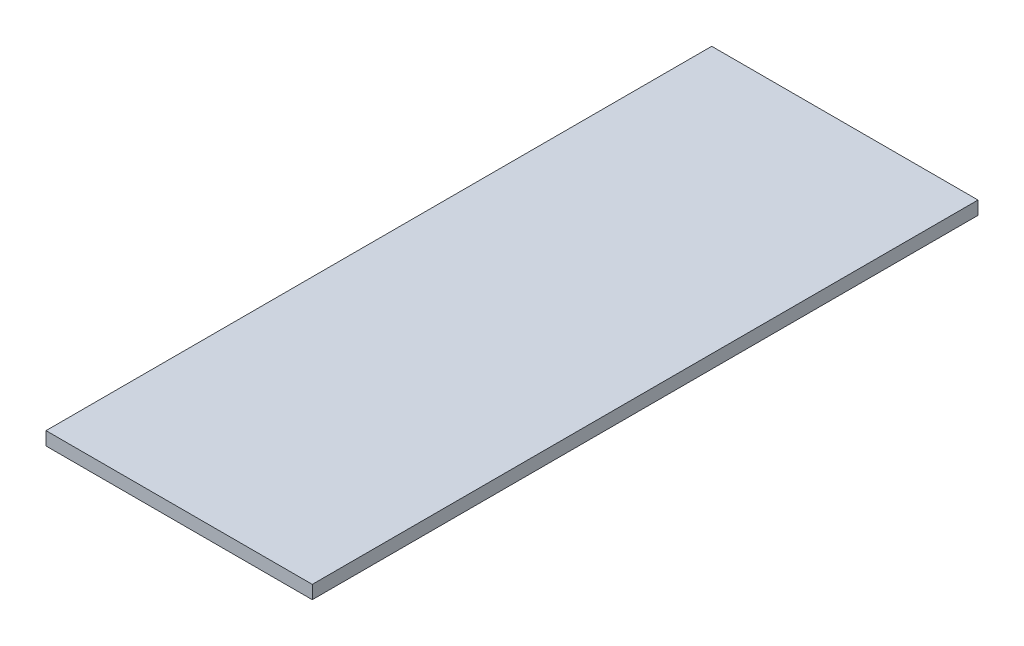
SolidWorks part; units mm, degrees
ref_plane "Piano frontale" through (0, 0, 0) normal (0, 0, 1) x (1, 0, 0)
ref_plane "Piano superiore" through (0, 0, 0) normal (0, 1, 0) x (1, 0, 0)
ref_plane "Piano destro" through (0, 0, 0) normal (1, 0, 0) x (0, 0, -1)
sketch "Schizzo1" plane through (0, 0, 0) normal (0, 1, 0) x (1, 0, 0)
  line L1 (0, 0) -> (400, 0)
  line L2 (0, 0) -> (0, 1000)
  line L3 (0, 1000) -> (400, 1000)
  line L4 (400, 0) -> (400, 1000)
  dimension "D1" = 400
  dimension "D2" = 1000
extrude "Estrusione-Estrusione1" add sketch "Schizzo1" along normal blind 20
sketch "Schizzo2" plane through (0, 0, 0) normal (0, -1, 0) x (-1, 0, 0)
  circle A0 centre (-200, 500) radius 20
extrude "Estrusione-Estrusione2" add sketch "Schizzo2" along normal blind 50 draft 12
sketch "Schizzo3" plane through (0, -50, 0) normal (0, -1, 0) x (-1, 0, 0)
  point P0 (-200, 500)
ref_plane "Piano1" through (200, 0, 0) normal (1, 0, 0) x (0, 0, -1)
sketch "Schizzo4" plane through (200, 0, 0) normal (1, 0, 0) x (0, 0, -1)
  line L0 (485, -60) -> (515, -60)
  line L1 (490.6278, -50) -> (509.3722, -50) construction
  arc A0 (515, -60) -> (485, -60) centre (500, -60) ccw
  dimension "D2" = 0
  dimension "D1" = 30
  dimension "D3" = 10
revolve "Rivoluzione1" add sketch "Schizzo4" angle 360 about L0
